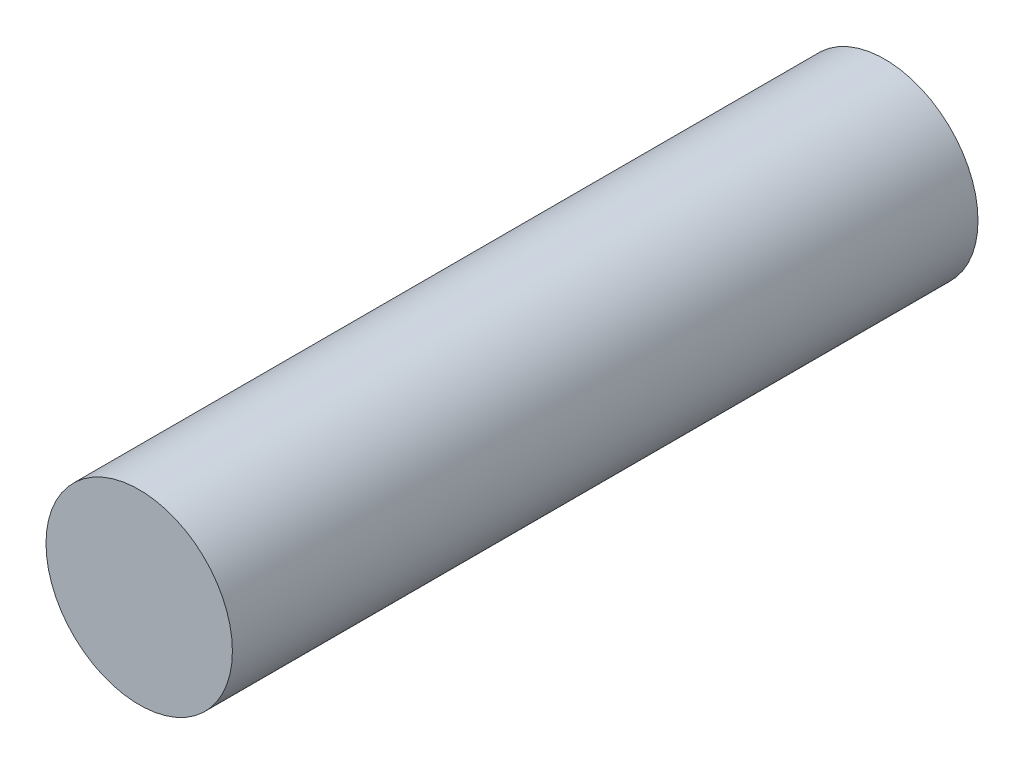
SolidWorks part; units mm, degrees
material "AISI 304"
ref_plane "Front Plane" through (0, 0, 0) normal (0, 0, 1) x (1, 0, 0)
ref_plane "Top Plane" through (0, 0, 0) normal (0, 1, 0) x (1, 0, 0)
ref_plane "Right Plane" through (0, 0, 0) normal (1, 0, 0) x (0, 0, -1)
sketch "Sketch1" plane through (0, 0, 0) normal (0, 0, 1) x (1, 0, 0)
  circle A0 centre (0, 0) radius 5
  dimension "D1" = 10
extrude "Boss-Extrude1" add sketch "Sketch1" along normal mid plane 40
